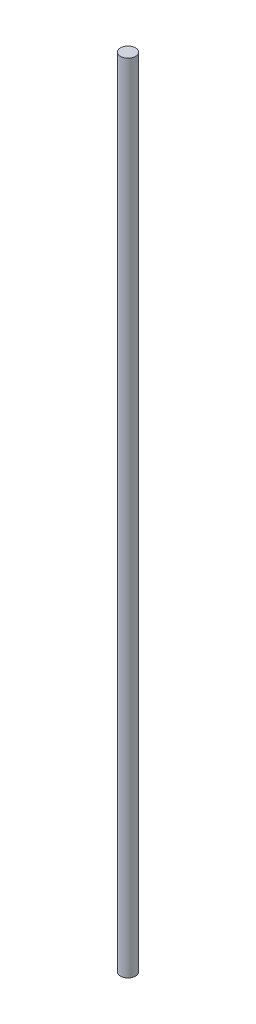
SolidWorks part; units mm, degrees
material "AISI 1020"
ref_plane "Front Plane" through (0, 0, 0) normal (0, 0, 1) x (1, 0, 0)
ref_plane "Top Plane" through (0, 0, 0) normal (0, 1, 0) x (1, 0, 0)
ref_plane "Right Plane" through (0, 0, 0) normal (1, 0, 0) x (0, 0, -1)
sketch "Sketch1" plane through (0, 0, 0) normal (0, 1, 0) x (1, 0, 0)
  circle A0 centre (0, 0) radius 4.7625
  dimension "D1" = 9.525
extrude "Boss-Extrude1" add sketch "Sketch1" against normal mid plane 508
